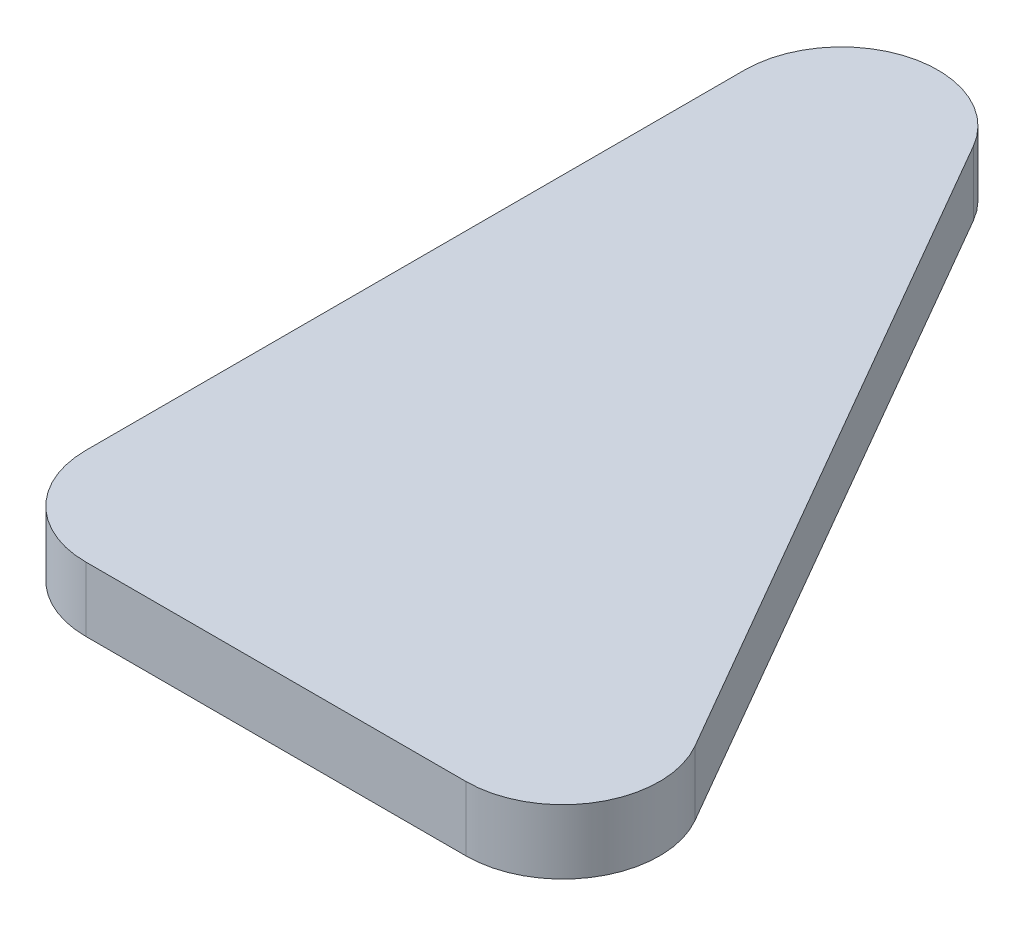
SolidWorks part; units mm, degrees
material "ABS PC"
ref_plane "Front Plane" through (0, 0, 0) normal (0, 0, 1) x (1, 0, 0)
ref_plane "Top Plane" through (0, 0, 0) normal (0, 1, 0) x (1, 0, 0)
ref_plane "Right Plane" through (0, 0, 0) normal (1, 0, 0) x (0, 0, -1)
sketch "Sketch1" plane through (0, 0, 0) normal (0, 1, 0) x (1, 0, 0)
  line L0 (-10, 17.32) -> (-10, -17.32)
  line L1 (-10, -17.32) -> (10, -17.32)
  line L2 (10, -17.32) -> (-10, 17.32)
  dimension "D1" = 20
  dimension "D2" = 34.64
extrude "Boss-Extrude1" add sketch "Sketch1" along normal blind 2
fillet "Fillet1" radius 3 3 edges at (-10, 1, -17.32) (-10, 1, 17.32) (10, 1, 17.32)
